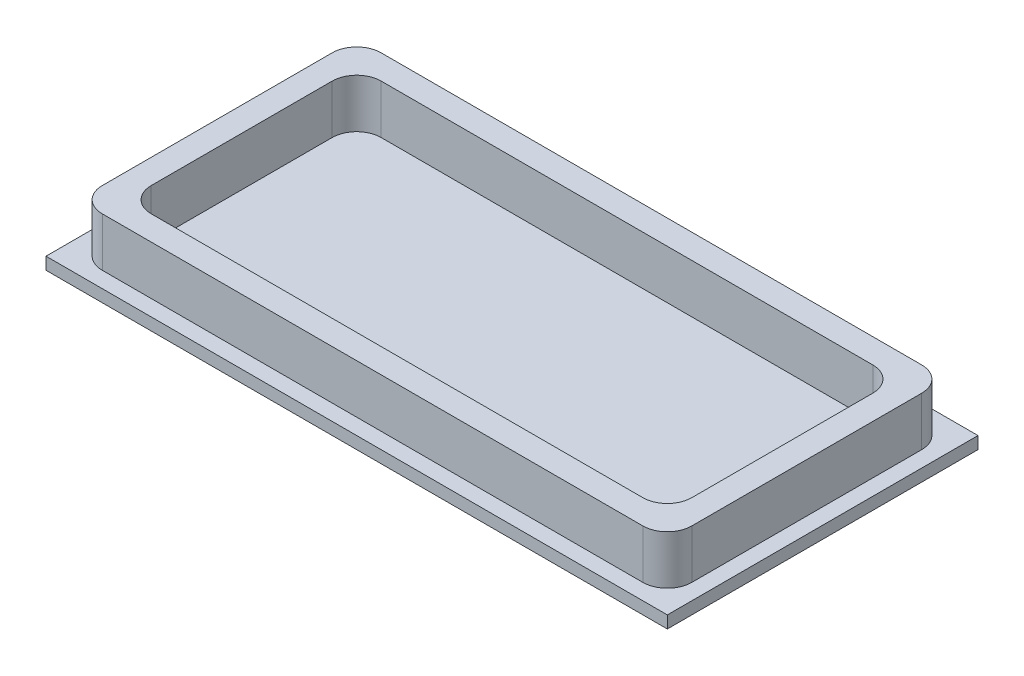
SolidWorks part; units mm, degrees
ref_plane "Front Plane" through (0, 0, 0) normal (0, 0, 1) x (1, 0, 0)
ref_plane "Top Plane" through (0, 0, 0) normal (0, 1, 0) x (1, 0, 0)
ref_plane "Right Plane" through (0, 0, 0) normal (1, 0, 0) x (0, 0, -1)
sketch "Sketch1" plane through (0, 0, 0) normal (0, 1, 0) x (1, 0, 0)
  line L1 (25.4, -12.7) -> (-25.4, -12.7)
  line L2 (25.4, -12.7) -> (25.4, 12.7)
  line L3 (25.4, 12.7) -> (-25.4, 12.7)
  line L4 (-25.4, -12.7) -> (-25.4, 12.7)
  line L5 (25.4, -12.7) -> (-25.4, 12.7) construction
  line L6 (25.4, 12.7) -> (-25.4, -12.7) construction
  point P0 (0, 0)
  dimension "D1" = 25.4
  dimension "D2" = 50.8
extrude "Boss-Extrude1" add sketch "Sketch1" along normal blind 1
sketch "Sketch2" plane through (0, 1, 0) normal (0, 1, 0) x (1, 0, 0)
  line L0 (-25.4, 12.7) -> (-25.4, -12.7) construction
  line L1 (-24.1, 11.4) -> (24.1, 11.4)
  line L2 (-24.1, 11.4) -> (-24.1, -11.4)
  line L3 (-24.1, -11.4) -> (24.1, -11.4)
  line L4 (24.1, 11.4) -> (24.1, -11.4)
  line L5 (-24.1, 11.4) -> (24.1, -11.4) construction
  line L6 (-24.1, -11.4) -> (24.1, 11.4) construction
  line L7 (25.4, 12.7) -> (-25.4, 12.7) construction
  line L8 (-22.1, 9.4) -> (-22.1, -9.4)
  line L9 (-22.1, -9.4) -> (22.1, -9.4)
  line L10 (22.1, 9.4) -> (22.1, -9.4)
  line L11 (-22.1, 9.4) -> (22.1, 9.4)
  point P0 (0, 0)
  dimension "D1" = 1.3
  dimension "D2" = 1.3
  dimension "D3" = 2
extrude "Boss-Extrude2" add sketch "Sketch2" along normal blind 4
fillet "Fillet1" radius 2 8 edges at (-22.1, 3, 9.4) (22.1, 3, 9.4) (22.1, 3, -9.4) (-22.1, 3, -9.4) (-24.1, 3, 11.4) (24.1, 3, 11.4) (24.1, 3, -11.4) (-24.1, 3, -11.4)
